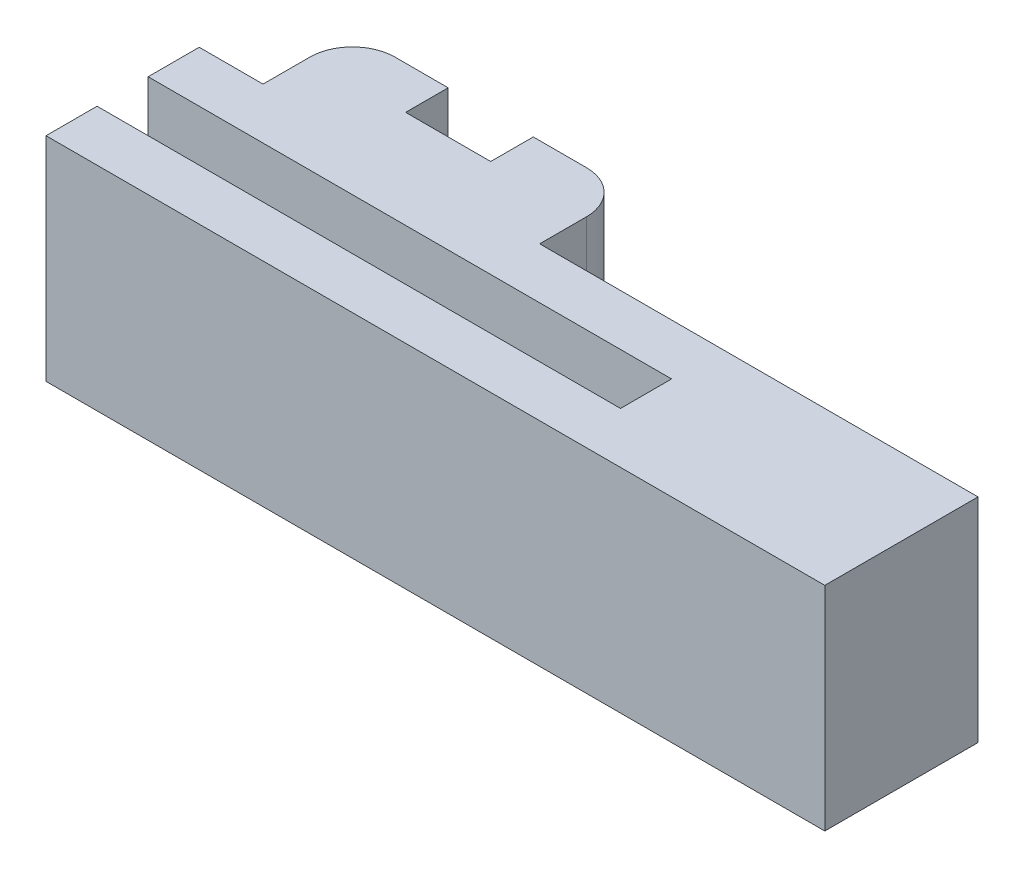
SolidWorks part; units mm, degrees
ref_plane "Front Plane" through (0, 0, 0) normal (0, 0, 1) x (1, 0, 0)
ref_plane "Top Plane" through (0, 0, 0) normal (0, 1, 0) x (1, 0, 0)
ref_plane "Right Plane" through (0, 0, 0) normal (1, 0, 0) x (0, 0, -1)
sketch "Sketch1" plane through (0, 0, 0) normal (0, 1, 0) x (1, 0, 0)
  line L0 (-8.7536, 4.1618) -> (-6.5036, 4.1618)
  line L1 (-14.5036, 2.0618) -> (-13.0036, 2.0618)
  line L2 (-14.5036, 2.0618) -> (-14.5036, 0.8618)
  line L3 (-14.5036, -1.5382) -> (3.7964, -1.5382)
  line L4 (3.7964, 2.0618) -> (3.7964, -1.5382)
  line L5 (-14.5036, -0.3382) -> (-14.5036, -1.5382)
  line L6 (-13.0036, 2.0618) -> (-13.0036, 4.1618)
  line L7 (-13.0036, 4.1618) -> (-10.7536, 4.1618)
  line L8 (-6.5036, 2.0618) -> (-6.5036, 4.1618)
  line L9 (-14.5036, 0.8618) -> (-2.2036, 0.8618)
  line L11 (-14.5036, -0.3382) -> (-2.2036, -0.3382)
  line L12 (-2.2036, 0.8618) -> (-2.2036, -0.3382)
  line L13 (-6.5036, 2.0618) -> (3.7964, 2.0618)
  line L14 (-10.7536, 4.1618) -> (-10.7536, 3.1618)
  line L15 (-10.7536, 3.1618) -> (-8.7536, 3.1618)
  line L16 (-8.7536, 4.1618) -> (-8.7536, 3.1618)
  dimension "D1" = 3.6
  dimension "D2" = 2.1
  dimension "D3" = 1
  dimension "D4" = 6.5
  dimension "D5" = 1.5
  dimension "D6" = 18.3
  dimension "D7" = 2
  dimension "D8" = 2.25
  dimension "D9" = 6
  dimension "D10" = 1.2
  dimension "D11" = 1.2
extrude "Boss-Extrude1" add sketch "Sketch1" along normal blind 5
fillet "Fillet1" radius 1 2 edges at (-6.5036, 2.5, -4.1618) (-13.0036, 2.5, -4.1618)
